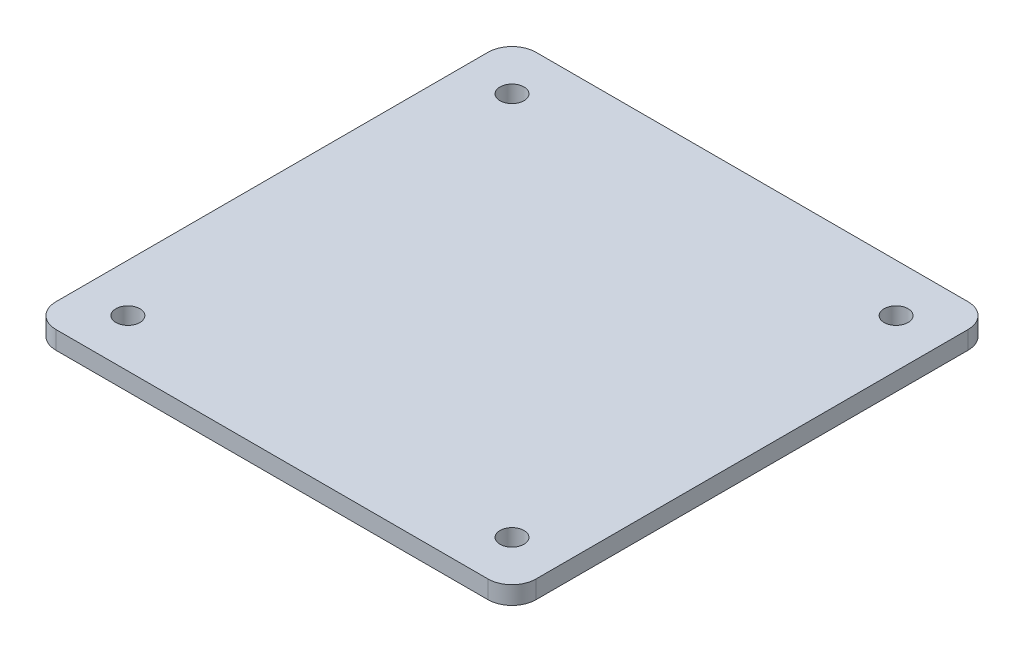
SolidWorks part; units mm, degrees
ref_plane "Plan de face" through (0, 0, 0) normal (0, 0, 1) x (1, 0, 0)
ref_plane "Plan de dessus" through (0, 0, 0) normal (0, 1, 0) x (1, 0, 0)
ref_plane "Plan de droite" through (0, 0, 0) normal (1, 0, 0) x (0, 0, -1)
sketch "Esquisse1" plane through (0, 0, 0) normal (0, 1, 0) x (1, 0, 0)
  line L1 (-36, 40) -> (36, 40)
  line L2 (-40, 36) -> (-40, -36)
  line L3 (-36, -40) -> (36, -40)
  line L4 (40, 36) -> (40, -36)
  line L5 (-40, 40) -> (40, -40) construction
  line L6 (-40, -40) -> (40, 40) construction
  arc A0 (36, 40) -> (40, 36) centre (36, 36) cw
  arc A1 (36, -40) -> (40, -36) centre (36, -36) ccw
  arc A2 (-40, -36) -> (-36, -40) centre (-36, -36) ccw
  arc A3 (-36, 40) -> (-40, 36) centre (-36, 36) ccw
  point P4 (0, 0)
  dimension "D2" = 4
  dimension "D1" = 80
extrude "Boss.-Extru.1" add sketch "Esquisse1" along normal blind 3
sketch "Esquisse2" plane through (0, 3, 0) normal (0, 1, 0) x (1, 0, 0)
  line L0 (36, 40) -> (-36, 40) construction
  line L1 (-40, 36) -> (-40, -36) construction
  circle A0 centre (-32, 32) radius 2
  circle A1 centre (32, 32) radius 2
  circle A2 centre (32, -32) radius 2
  circle A3 centre (-32, -32) radius 2
  point P12 (0, 0)
  dimension "D1" = 4
  dimension "D3" = 8
  dimension "D4" = 8
  dimension "D2" = 4
extrude "Enlèv. mat.-Extru.1" cut sketch "Esquisse2" against normal through all
